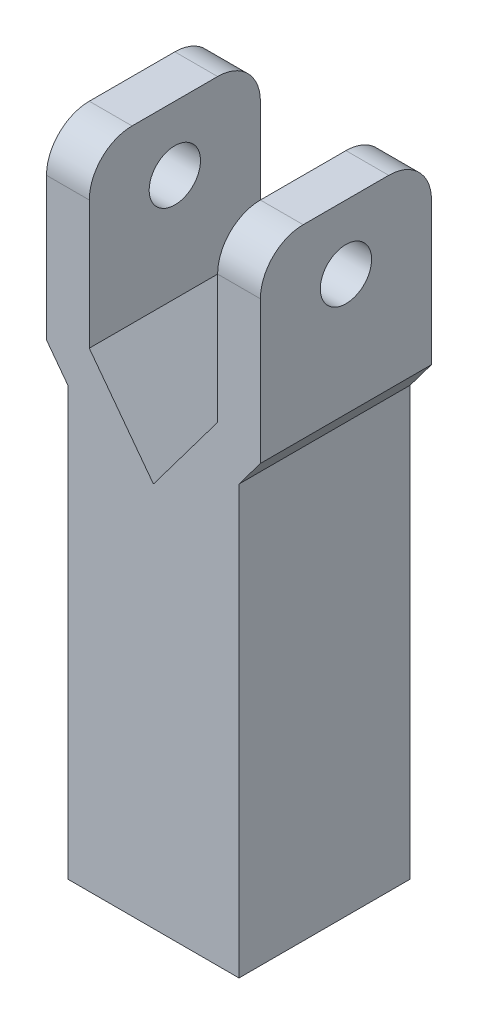
SolidWorks part; units mm, degrees
material "FE360"
ref_plane "Piano frontale" through (0, 0, 0) normal (0, 0, 1) x (1, 0, 0)
ref_plane "Piano superiore" through (0, 0, 0) normal (0, 1, 0) x (1, 0, 0)
ref_plane "Piano destro" through (0, 0, 0) normal (1, 0, 0) x (0, 0, -1)
sketch "Schizzo1" plane through (0, 0, 0) normal (0, 0, 1) x (1, 0, 0)
  line L0 (-25, 150) -> (-25, 106.6667)
  line L1 (-25, 106.6667) -> (-20, 100)
  line L2 (-20, 100) -> (-20, 0)
  line L3 (-20, 0) -> (0, 0)
  line L4 (0, 0) -> (0, 90)
  line L5 (-15, 150) -> (-25, 150)
  line L6 (-15, 150) -> (-15, 110)
  line L7 (-15, 110) -> (0, 90)
  dimension "D1" = 10
  dimension "D2" = 20
  dimension "D3" = 10
  dimension "D4" = 100
  dimension "D5" = 90
  dimension "D6" = 150
  dimension "D7" = 15
extrude "Estrusione-Estrusione1" add sketch "Schizzo1" along normal mid plane 40
sketch "Schizzo2" plane through (-25, 0, 0) normal (-1, 0, 0) x (0, 0, 1)
  line L0 (20, 150) -> (-20, 150) construction
  circle A0 centre (0, 135) radius 6
  dimension "D1" = 12
  dimension "D2" = 15
extrude "Taglio-Estrusione1" cut sketch "Schizzo2" against normal blind 40
mirror "Specchia1" about plane through (0, 0, 20) normal (-1, 0, 0) of bodies 106
fillet "Raccordo1" radius 10 4 edges at (20, 150, -20) (20, 150, 20) (-20, 150, -20) (-20, 150, 20)
